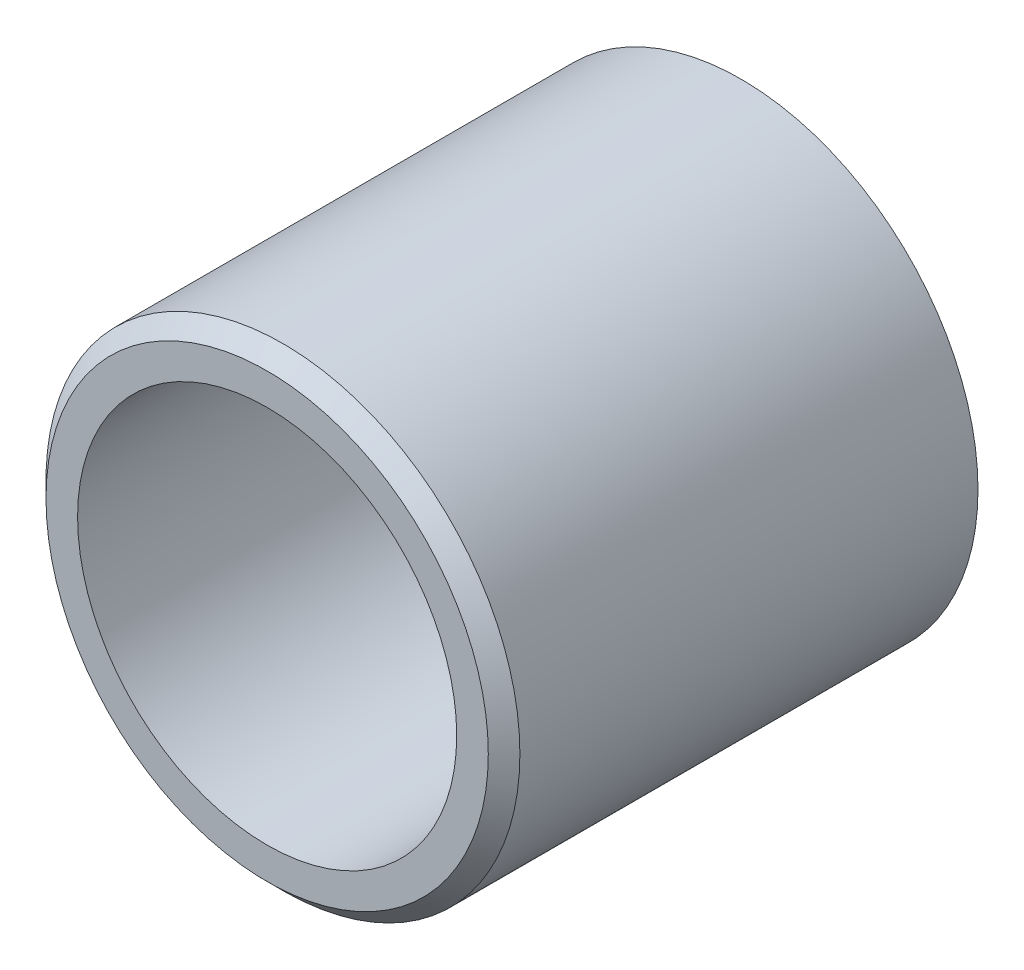
SolidWorks part; units mm, degrees
ref_plane "Front Plane" through (0, 0, 0) normal (0, 0, 1) x (1, 0, 0)
ref_plane "Top Plane" through (0, 0, 0) normal (0, 1, 0) x (1, 0, 0)
ref_plane "Right Plane" through (0, 0, 0) normal (1, 0, 0) x (0, 0, -1)
sketch "Sketch1" plane through (0, 0, 0) normal (0, 0, 1) x (1, 0, 0)
  circle A0 centre (0, 0) radius 7.5
  circle A1 centre (0, 0) radius 6
  dimension "D1" = 15
  dimension "D2" = 12
extrude "Boss-Extrude1" add sketch "Sketch1" along normal blind 15
chamfer "Chamfer2" distance 0.5 angle 45 1 edges at (7.5, 0, 15)
